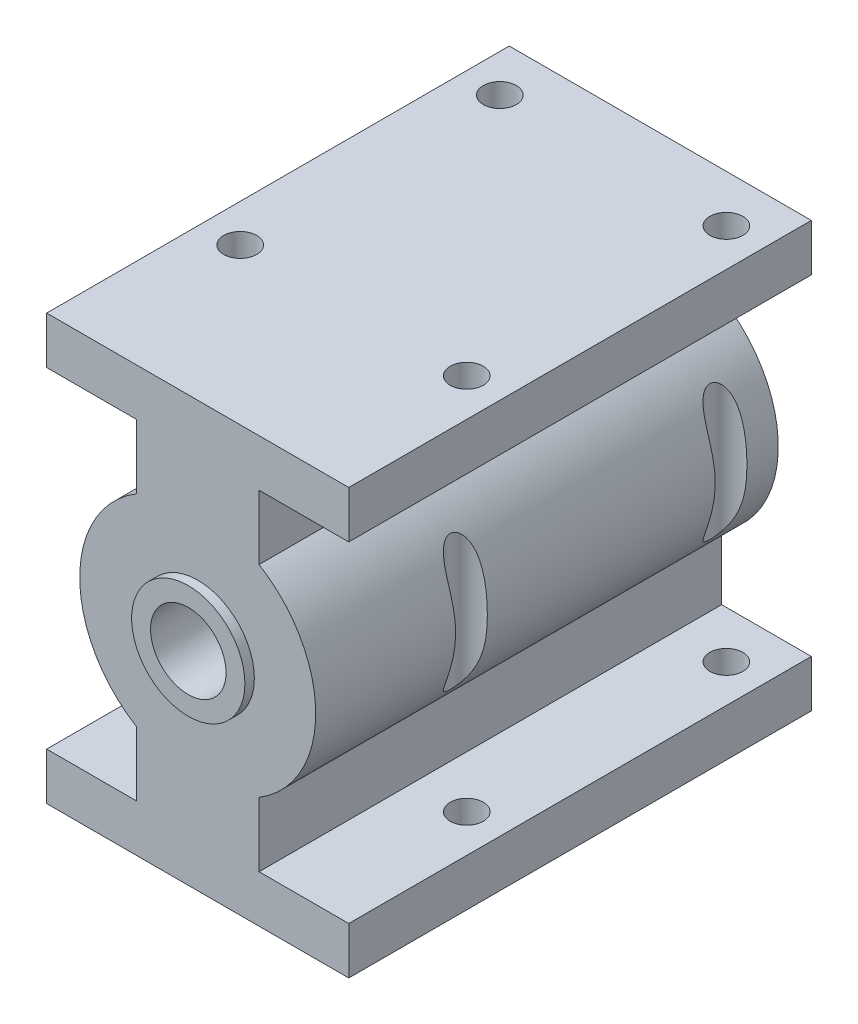
SolidWorks part; units mm, degrees
ref_plane "Front Plane" through (0, 0, 0) normal (0, 0, 1) x (1, 0, 0)
ref_plane "Top Plane" through (0, 0, 0) normal (0, 1, 0) x (1, 0, 0)
ref_plane "Right Plane" through (0, 0, 0) normal (1, 0, 0) x (0, 0, -1)
sketch "Sketch1" plane through (0, 0, 0) normal (0, 0, 1) x (1, 0, 0)
  line L0 (-6.5, 17.5) -> (6.5, 17.5)
  line L2 (-6.5, 17.5) -> (-6.5, 10.6771)
  line L4 (6.5, 17.5) -> (6.5, 10.6771)
  line L5 (3.6394, 0) -> (0, 0) construction
  line L6 (-6.5, -17.5) -> (6.5, -17.5)
  line L7 (-6.5, -10.6771) -> (-6.5, -17.5)
  line L9 (6.5, -10.6771) -> (6.5, -17.5)
  arc A0 (-6.5, 10.6771) -> (-6.5, -10.6771) centre (0, 0) ccw
  arc A1 (6.5, -10.6771) -> (6.5, 10.6771) centre (0, 0) ccw
  point P0 (0, 0)
  dimension "D3" = 25
  dimension "D2" = 17.5
extrude "Boss-Extrude1" add sketch "Sketch1" along normal blind 49
sketch "Sketch2" plane through (0, 0, 49) normal (0, 0, 1) x (1, 0, 0)
  circle A0 centre (0, 0) radius 4
  dimension "D1" = 8
extrude "Cut-Extrude1" cut sketch "Sketch2" against normal blind 47
sketch "Sketch7" plane through (0, 0, 0) normal (0, 0, 1) x (1, 0, 0)
  line L0 (6.7865, 0) -> (0, 0) construction
  line L1 (-16, 22.5) -> (16, 22.5)
  line L2 (-16, 22.5) -> (-16, 17.5)
  line L3 (-16, 17.5) -> (16, 17.5)
  line L4 (16, 22.5) -> (16, 17.5)
  line L5 (-16, 22.5) -> (16, 17.5) construction
  line L6 (-16, 17.5) -> (16, 22.5) construction
  line L7 (-16, -17.5) -> (16, -22.5) construction
  line L8 (-16, -22.5) -> (16, -17.5) construction
  line L9 (16, -22.5) -> (16, -17.5)
  line L10 (-16, -17.5) -> (16, -17.5)
  line L11 (-16, -22.5) -> (-16, -17.5)
  line L12 (-16, -22.5) -> (16, -22.5)
  point P0 (0, 20)
  point P12 (0, -20)
  dimension "D1" = 5
  dimension "D2" = 32
  dimension "D3" = 16
  dimension "D4" = 17.5
extrude "Boss-Extrude2" add sketch "Sketch7" along normal blind 49
sketch "Sketch8" plane through (0, 22.5, 0) normal (0, 1, 0) x (1, 0, 0)
  line L0 (16, -49) -> (-16, -49) construction
  line L1 (16, 0) -> (-16, 0) construction
  line L2 (-16, -49) -> (-16, 0) construction
  line L3 (0, -19.5999) -> (0, -25.7226) construction
  circle A0 centre (-12, -5) radius 1.75
  circle A1 centre (-12, -32.5) radius 1.75
  circle A2 centre (12, -32.5) radius 1.75
  circle A3 centre (12, -5) radius 1.75
  dimension "D3" = 3.5
  dimension "D6" = 3.5
  dimension "D1" = 16.5
  dimension "D2" = 5
  dimension "D4" = 4
  dimension "D5" = 4
extrude "Cut-Extrude4" cut sketch "Sketch8" against normal through all
sketch "Sketch9" plane through (0, 0, 49) normal (0, 0, 1) x (1, 0, 0)
  circle A0 centre (0, 0) radius 4
  circle A1 centre (0, 0) radius 6
  dimension "D1" = 12
extrude "Boss-Extrude3" add sketch "Sketch9" along normal blind 1
